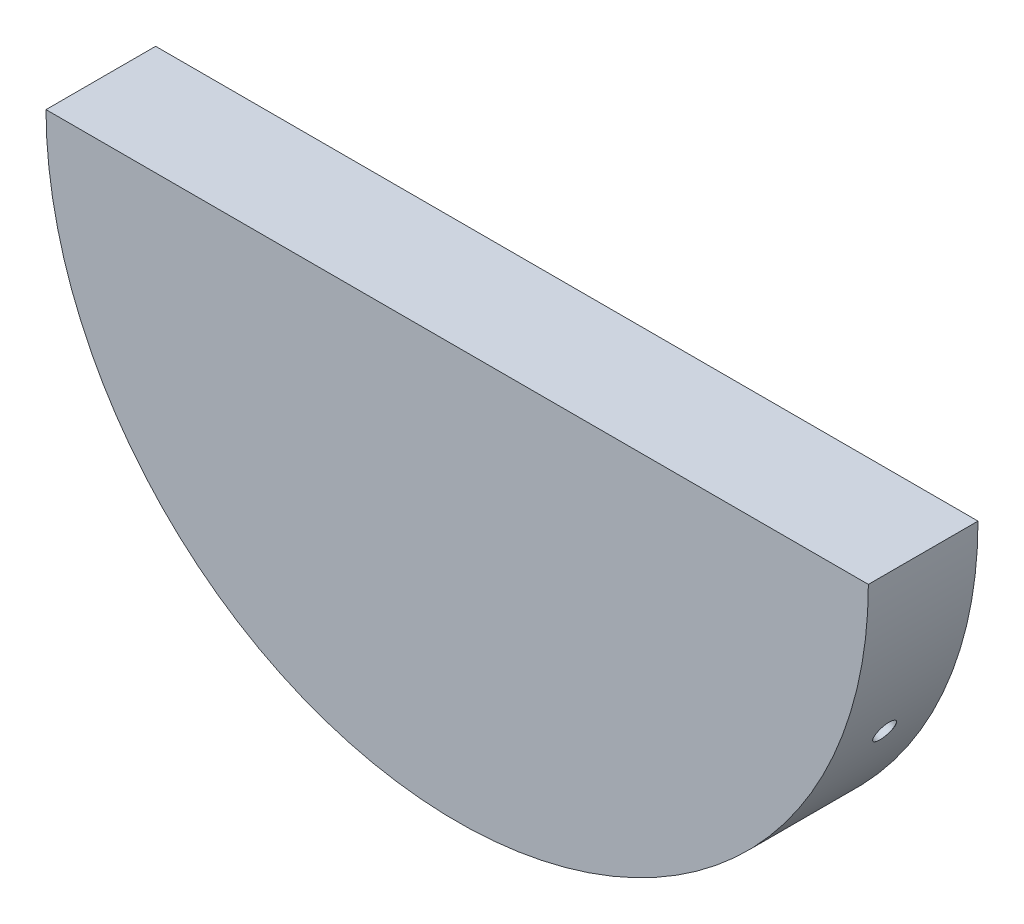
SolidWorks part; units mm, degrees
ref_plane "Front Plane" through (0, 0, 0) normal (0, 0, 1) x (1, 0, 0)
ref_plane "Top Plane" through (0, 0, 0) normal (0, 1, 0) x (1, 0, 0)
ref_plane "Right Plane" through (0, 0, 0) normal (1, 0, 0) x (0, 0, -1)
sketch "Sketch1" plane through (0, 0, 0) normal (0, 0, 1) x (1, 0, 0)
  line L0 (-150, 0) -> (0, 0)
  arc A1 (-150, 0) -> (0, 0) centre (-75, 0) ccw
  dimension "D7" = 75
extrude "Boss-Extrude1" add sketch "Sketch1" along normal blind 20
hole_wizard "Ø4.0mm Dowel Hole2" positions "3DSketch2" profile "Sketch4" hole size "Ø4.0" standard "ANSI Metric"
sketch3d "3DSketch2"
  line L2 (0, 0, 20) -> (0, 0, 0) construction
  line L4 (0, 0, 20) -> (0, 0, 0) construction
  line L5 (0, 0, 10) -> (-7.0269, -31.6964, 10) construction
  line L8 (-75, 0, 0) -> (-75, 0, 20) construction
  line L9 (0, 0, 0) -> (-150, 0, 0) construction
  line L10 (0, 0, 20) -> (-150, 0, 20) construction
  line L12 (-75, 0, 10) -> (-7.0269, -31.6964, 10) construction
  line L16 (-75, 0, 10) -> (0, 0, 10) construction
  point P0 (-7.0269, -31.6964, 10)
  point P16 (-7.0269, -31.6964, 10)
  point P23 (-7.0269, -31.6964, 10)
  point P25 (-7.0269, -31.6964, 10)
  dimension "D1" = 25
sketch "Sketch4" plane through (-7.0269, -31.6964, 10) normal (0, 0, 1) x (0.4226, 0.9063, 0)
  line L0 (0, 0) -> (0, 17.2017)
  line L1 (0, 17.2017) -> (2, 16)
  line L2 (2, 16) -> (2, 0.025)
  line L3 (2, 0.025) -> (2.025, 0)
  line L5 (2.025, 0) -> (0, 0)
  line L6 (-2, 0.025) -> (-2.025, 0) construction
  line L10 (0, 17.2017) -> (-2, 16) construction
  line L11 (0, -6.35) -> (0, 107.95) construction
  dimension "Hole Dia." = 4
  dimension "Hole Depth" = 16
  dimension "Near C'Sink Dia." = 4.05
  dimension "Near C'Sink Angle" = 90
  dimension "Drill Angle" = 118
pattern_circular "CirPattern1" count 5 over 130 about axis through (-75, 0, 0) along (0, 0, 1) of "Ø4.0mm Dowel Hole2"
